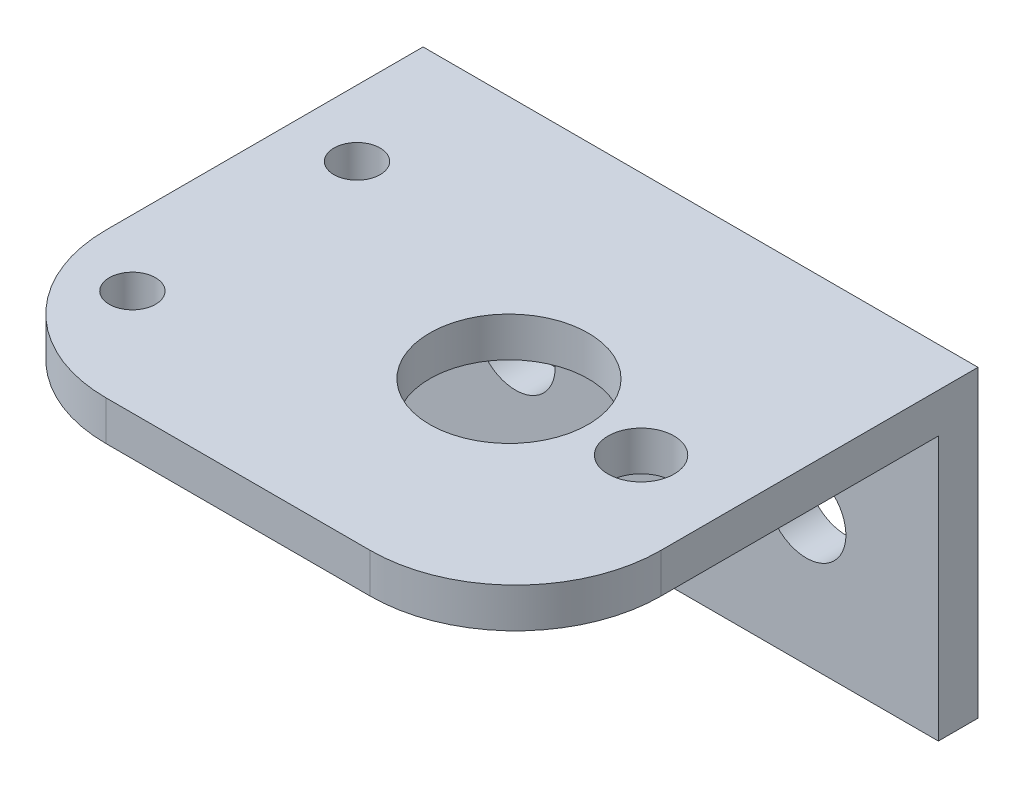
SolidWorks part; units mm, degrees
ref_plane "Front Plane" through (0, 0, 0) normal (0, 0, 1) x (1, 0, 0)
ref_plane "Top Plane" through (0, 0, 0) normal (0, 1, 0) x (1, 0, 0)
ref_plane "Right Plane" through (0, 0, 0) normal (1, 0, 0) x (0, 0, -1)
sketch "Sketch1" plane through (0, 0, 0) normal (0, 1, 0) x (1, 0, 0)
  line L0 (5, -10) -> (5, -27) construction
  line L1 (0, 0) -> (42, 0)
  line L2 (0, 0) -> (0, -35)
  line L3 (0, -35) -> (42, -35)
  line L4 (42, 0) -> (42, -35)
  line L5 (5, -18.5) -> (78.5425, -18.5) construction
  line L6 (76.0507, 18.6222) -> (80.4984, -47.6371) construction
  circle A0 centre (5, -10) radius 1.75
  circle A1 centre (5, -27) radius 1.75
  circle A2 centre (25, -18.5) radius 6
  circle A3 centre (35, -18.5) radius 2.5
  dimension "D6" = 3.5
  dimension "D7" = 3.5
  dimension "D10" = 12
  dimension "D11" = 5
  dimension "D1" = 42
  dimension "D2" = 35
  dimension "D3" = 17
  dimension "D4" = 10
  dimension "D5" = 5
  dimension "D8" = 20
  dimension "D9" = 30
extrude "Boss-Extrude1" add sketch "Sketch1" along normal blind 3
sketch "Sketch2" plane through (0, 0, 0) normal (0, -1, 0) x (1, 0, 0)
  line L0 (42, 35) -> (42, 0) construction
  line L1 (0, 0) -> (42, 0)
  line L2 (0, 0) -> (0, 3)
  line L3 (0, 3) -> (42, 3)
  line L4 (42, 0) -> (42, 3)
  dimension "D1" = 3
extrude "Boss-Extrude2" add sketch "Sketch2" along normal blind 20
sketch "Sketch3" plane through (0, 0, 0) normal (0, 0, -1) x (-1, 0, 0)
  line L0 (-42, 3) -> (-42, -20) construction
  line L1 (0, 3) -> (0, -20) construction
  line L2 (-42, 0) -> (0, 0) construction
  line L3 (-42, 0) -> (0, 0) construction
  circle A0 centre (-32, -10) radius 3
  circle A1 centre (-10, -10) radius 3
  dimension "D1" = 6
  dimension "D2" = 6
  dimension "D3" = 10
  dimension "D4" = 10
  dimension "D5" = 10
  dimension "D6" = 10
extrude "Cut-Extrude1" cut sketch "Sketch3" against normal blind 20
fillet "Fillet1" radius 11 2 edges at (42, 1.5, 35) (0, 1.5, 35)
